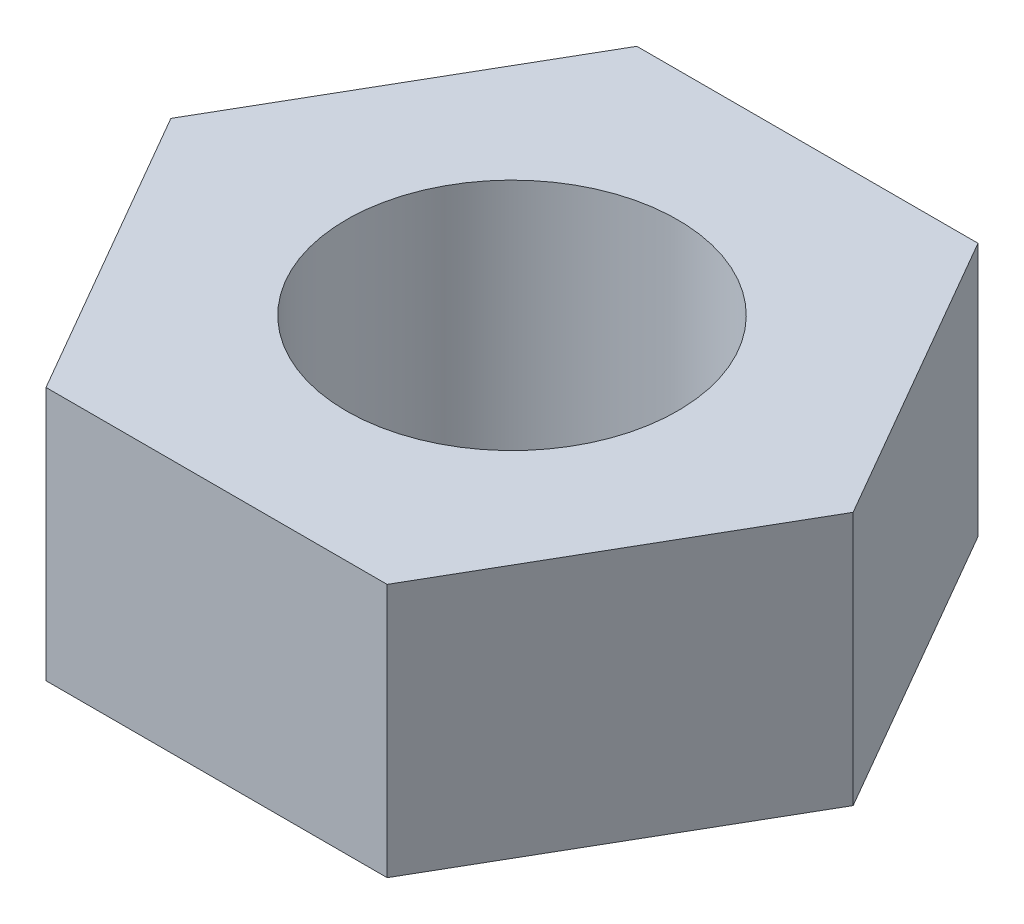
SolidWorks part; units mm, degrees
ref_plane "Front Plane" through (0, 0, 0) normal (0, 0, 1) x (1, 0, 0)
ref_plane "Top Plane" through (0, 0, 0) normal (0, 1, 0) x (1, 0, 0)
ref_plane "Right Plane" through (0, 0, 0) normal (1, 0, 0) x (0, 0, -1)
sketch "Sketch1" plane through (0, 0, 0) normal (0, 1, 0) x (1, 0, 0)
  line L1 (3.0888, 0) -> (1.5444, 2.675)
  line L2 (1.5444, 2.675) -> (-1.5444, 2.675)
  line L3 (-1.5444, 2.675) -> (-3.0888, 0)
  line L4 (-3.0888, 0) -> (-1.5444, -2.675)
  line L5 (-1.5444, -2.675) -> (1.5444, -2.675)
  line L6 (1.5444, -2.675) -> (3.0888, 0)
  circle A0 centre (0, 0) radius 2.675 construction
  point P1 (3.0888, 0)
  dimension "D1" = 5.35
extrude "Boss-Extrude1" add sketch "Sketch1" along normal blind 2.3
sketch "Sketch2" plane through (0, 2.3, 0) normal (0, 1, 0) x (1, 0, 0)
  circle A0 centre (0, 0) radius 1.5
  dimension "D1" = 3
extrude "Cut-Extrude1" cut sketch "Sketch2" against normal through all
